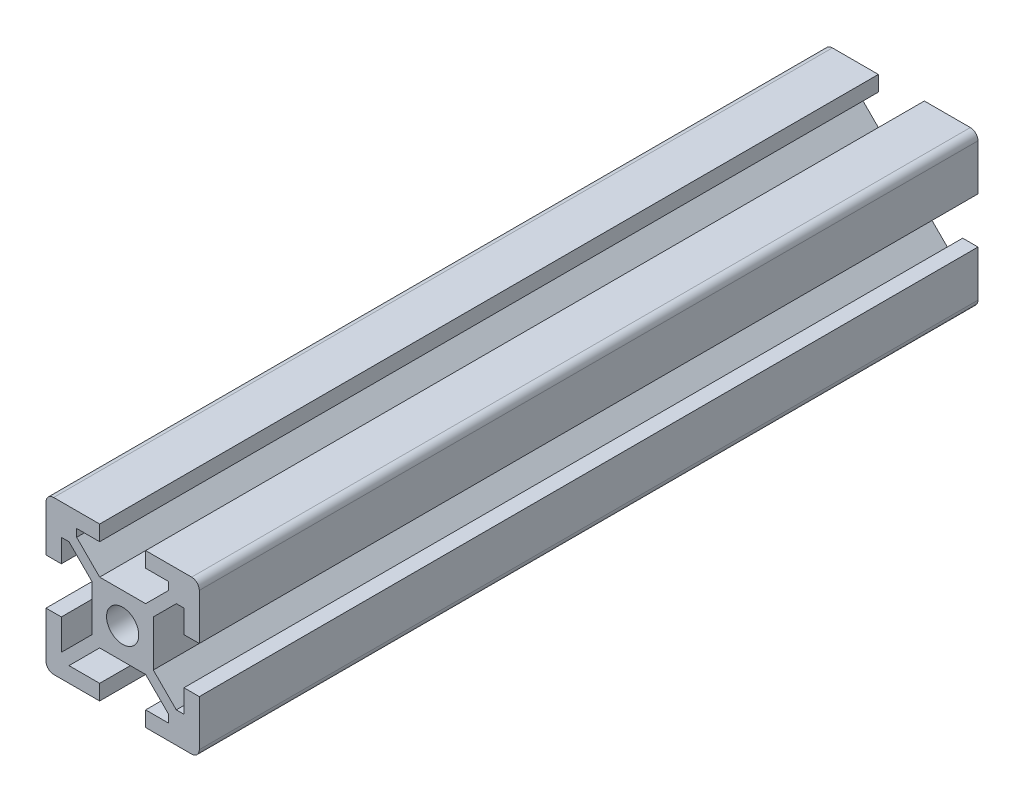
SolidWorks part; units mm, degrees
ref_plane "Front Plane" through (0, 0, 0) normal (0, 0, 1) x (1, 0, 0)
ref_plane "Top Plane" through (0, 0, 0) normal (0, 1, 0) x (1, 0, 0)
ref_plane "Right Plane" through (0, 0, 0) normal (1, 0, 0) x (0, 0, -1)
sketch "Sketch1" plane through (0, 0, 0) normal (0, 0, 1) x (1, 0, 0)
  line L0 (0, 10) -> (0, -10) construction
  line L1 (10, 10) -> (-10, 10)
  line L2 (10, 10) -> (10, -10)
  line L3 (10, -10) -> (-10, -10)
  line L4 (-10, 10) -> (-10, -10)
  line L5 (10, 10) -> (-10, -10) construction
  line L6 (10, -10) -> (-10, 10) construction
  line L7 (-10, 0) -> (10, 0) construction
  line L8 (-4, 3) -> (-8, 7)
  line L9 (6, 6) -> (-6, 6)
  line L10 (6, 6) -> (6, -6)
  line L11 (6, -6) -> (-6, -6)
  line L12 (-6, 6) -> (-6, -6)
  line L13 (6, 6) -> (-6, -6) construction
  line L14 (6, -6) -> (-6, 6) construction
  line L15 (4, 4) -> (-4, 4)
  line L16 (4, 4) -> (4, -4)
  line L17 (4, -4) -> (-4, -4)
  line L18 (-4, 4) -> (-4, -4)
  line L19 (4, 4) -> (-4, -4) construction
  line L20 (4, -4) -> (-4, 4) construction
  line L21 (3, 10) -> (-3, 10)
  line L22 (3, 10) -> (3, -10)
  line L23 (3, -10) -> (-3, -10)
  line L24 (-3, 10) -> (-3, -10)
  line L25 (3, 10) -> (-3, -10) construction
  line L26 (3, -10) -> (-3, 10) construction
  line L27 (10, 3) -> (-10, 3)
  line L28 (10, 3) -> (10, -3)
  line L29 (10, -3) -> (-10, -3)
  line L30 (-10, 3) -> (-10, -3)
  line L31 (10, 3) -> (-10, -3) construction
  line L32 (10, -3) -> (-10, 3) construction
  line L33 (8, 8) -> (-8, 8)
  line L34 (8, 8) -> (8, -8)
  line L35 (8, -8) -> (-8, -8)
  line L36 (-8, 8) -> (-8, -8)
  line L37 (8, 8) -> (-8, -8) construction
  line L38 (8, -8) -> (-8, 8) construction
  line L39 (-3, 4) -> (-7, 8)
  line L40 (3, 4) -> (7, 8)
  line L41 (4, 3) -> (8, 7)
  line L42 (-4, -3) -> (-8, -7)
  line L43 (-3, -4) -> (-7, -8)
  line L44 (3, -4) -> (7, -8)
  line L45 (4, -3) -> (8, -7)
  line L46 (-6, 6) -> (-6, 8)
  line L47 (-6, 6) -> (-8, 6)
  line L48 (-6, -6) -> (-8, -6)
  line L49 (-6, -6) -> (-6, -8)
  line L50 (6, -6) -> (6, -8)
  line L51 (6, -6) -> (8, -6)
  line L52 (6, 6) -> (6, 8)
  line L53 (6, 6) -> (8, 6)
  circle A0 centre (0, 0) radius 2.1
  point P0 (0, 0)
  point P10 (0, 0)
  point P15 (0, 0)
  point P20 (0, 0)
  point P25 (0, 0)
  point P30 (0, 0)
  dimension "D11" = 4.2
  dimension "D1" = 20
  dimension "D2" = 20
  dimension "D3" = 12
  dimension "D4" = 12
  dimension "D5" = 8
  dimension "D6" = 8
  dimension "D7" = 6
  dimension "D8" = 6
  dimension "D9" = 2
  dimension "D10" = 2
extrude "Boss-Extrude1" add sketch "Sketch1" along normal blind 101.6 contours L39 L46 L33 | L47 L46 L39 L33 L36 L8 | L47 L8 L36 | L36 L33 L24 L1 L4 L27 | L12 L47 L8 | L46 L9 L39 | L15 L39 L9 L12 L8 L18 | L27 L24 L15 L18 | L27 L22 L15 L24 | L29 L24 L27 L18 | L29 L22 L27 L24 A0 | L27 L16 L15 L22 | L16 L41 L10 L9 L40 L15 | L9 L52 L40 | L53 L10 L41 | L52 L53 L41 L34 L33 L40 | L52 L40 L33 | L41 L53 L34 | L33 L34 L27 L2 L1 L22 | L29 L16 L27 L22 | L16 L29 L22 L17 | L45 L16 L17 L44 L11 L10 | L10 L51 L45 | L50 L11 L44 | L51 L50 L44 L35 L34 L45 | L44 L50 L35 | L51 L45 L34 | L34 L35 L22 L3 L2 L29 | L22 L29 L24 L17 | L24 L29 L18 L17 | L43 L17 L18 L42 L12 L11 | L11 L49 L43 | L48 L12 L42 | L49 L48 L42 L36 L35 L43 | L36 L29 L4 L3 L24 L35
fillet "Fillet1" radius 1 4 edges at (-10, -10, 50.8) (10, -10, 50.8) (10, 10, 50.8) (-10, 10, 50.8)
